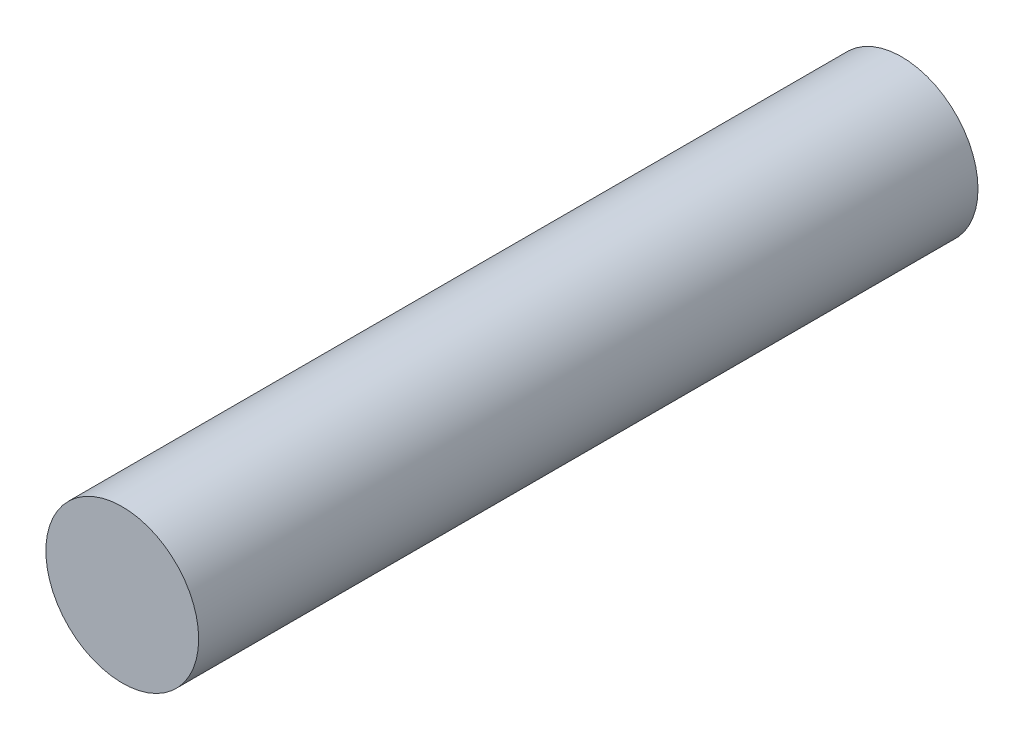
SolidWorks part; units mm, degrees
ref_plane "Front Plane" through (0, 0, 0) normal (0, 0, 1) x (1, 0, 0)
ref_plane "Top Plane" through (0, 0, 0) normal (0, 1, 0) x (1, 0, 0)
ref_plane "Right Plane" through (0, 0, 0) normal (1, 0, 0) x (0, 0, -1)
sketch "Sketch1" plane through (0, 0, 0) normal (0, 0, 1) x (1, 0, 0)
  circle A0 centre (0, 0) radius 75
  dimension "D1" = 150
extrude "Boss-Extrude1" add sketch "Sketch1" against normal blind 765
